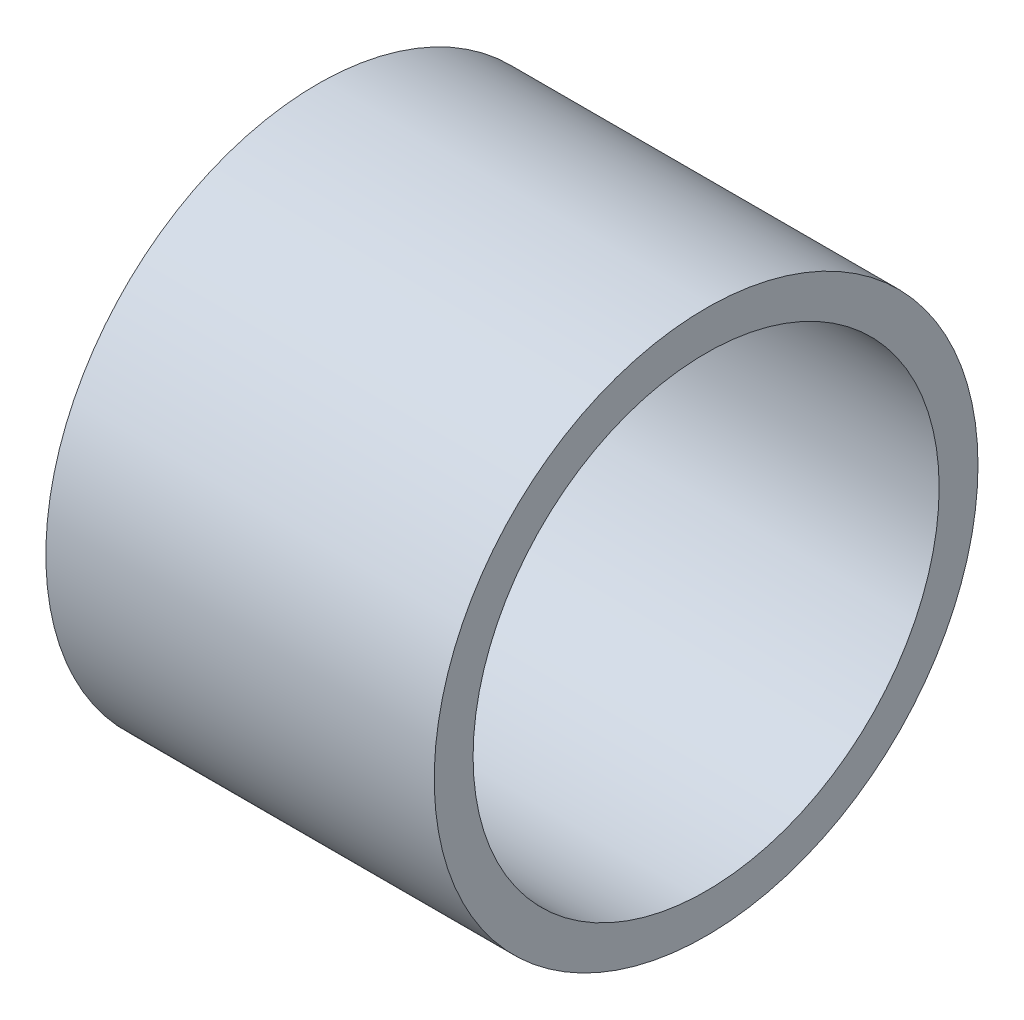
SolidWorks part; units mm, degrees
material "Brass"
ref_plane "Front Plane" through (0, 0, 0) normal (0, 0, 1) x (1, 0, 0)
ref_plane "Top Plane" through (0, 0, 0) normal (0, 1, 0) x (1, 0, 0)
ref_plane "Right Plane" through (0, 0, 0) normal (1, 0, 0) x (0, 0, -1)
sketch "Sketch1" plane through (0, 0, 0) normal (1, 0, 0) x (0, 0, -1)
  circle A0 centre (0, 0) radius 3
  circle A1 centre (0, 0) radius 3.5
  dimension "D1" = 7
  dimension "D2" = 6
extrude "Boss-Extrude1" add sketch "Sketch1" along normal blind 5
